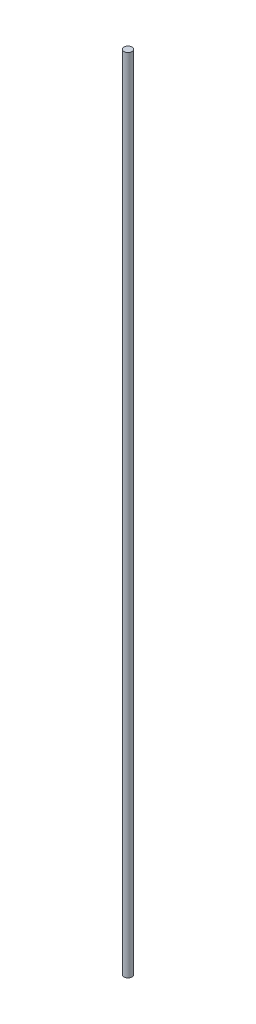
SolidWorks part; units mm, degrees
ref_plane "Front Plane" through (0, 0, 0) normal (0, 0, 1) x (1, 0, 0)
ref_plane "Top Plane" through (0, 0, 0) normal (0, 1, 0) x (1, 0, 0)
ref_plane "Right Plane" through (0, 0, 0) normal (1, 0, 0) x (0, 0, -1)
sketch "Sketch1" plane through (0, 0, 0) normal (0, 1, 0) x (1, 0, 0)
  circle A0 centre (0, 0) radius 2
  dimension "D1" = 4
extrude "Boss-Extrude1" add sketch "Sketch1" along normal blind 400
